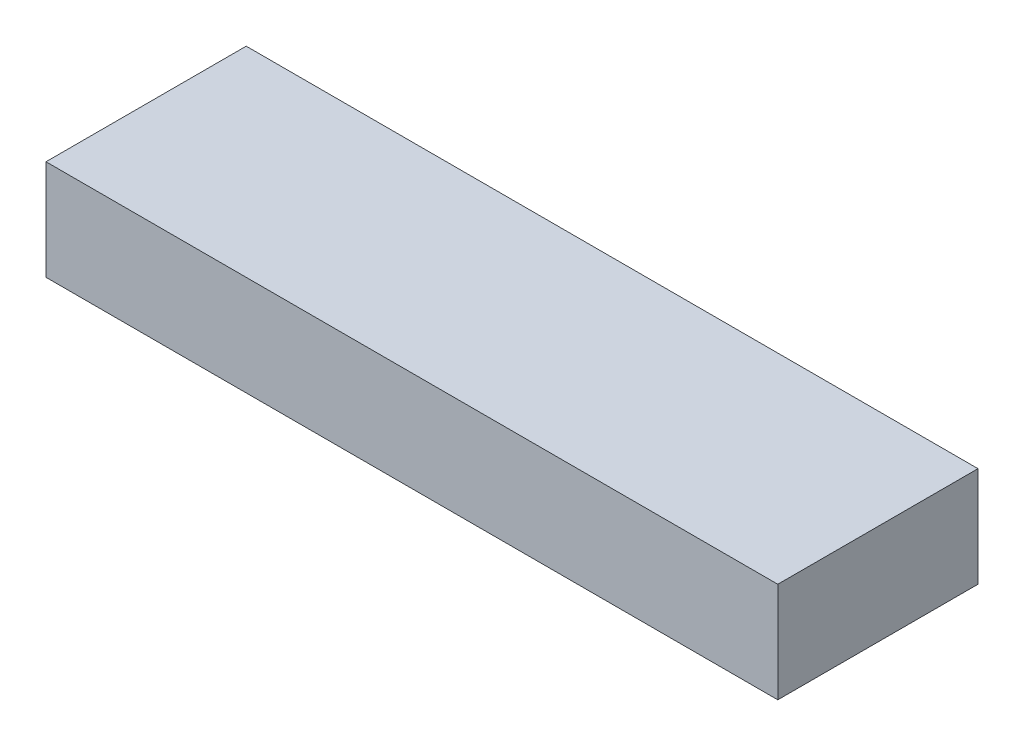
SolidWorks part; units mm, degrees
ref_plane "Front Plane" through (0, 0, 0) normal (0, 0, 1) x (1, 0, 0)
ref_plane "Top Plane" through (0, 0, 0) normal (0, 1, 0) x (1, 0, 0)
ref_plane "Right Plane" through (0, 0, 0) normal (1, 0, 0) x (0, 0, -1)
sketch "Sketch1" plane through (0, 0, 0) normal (0, 1, 0) x (1, 0, 0)
  line L1 (0, 0) -> (73.1, 0)
  line L2 (0, 0) -> (0, 20)
  line L3 (0, 20) -> (73.1, 20)
  line L4 (73.1, 0) -> (73.1, 20)
extrude "Boss-Extrude1" add sketch "Sketch1" against normal blind 10
